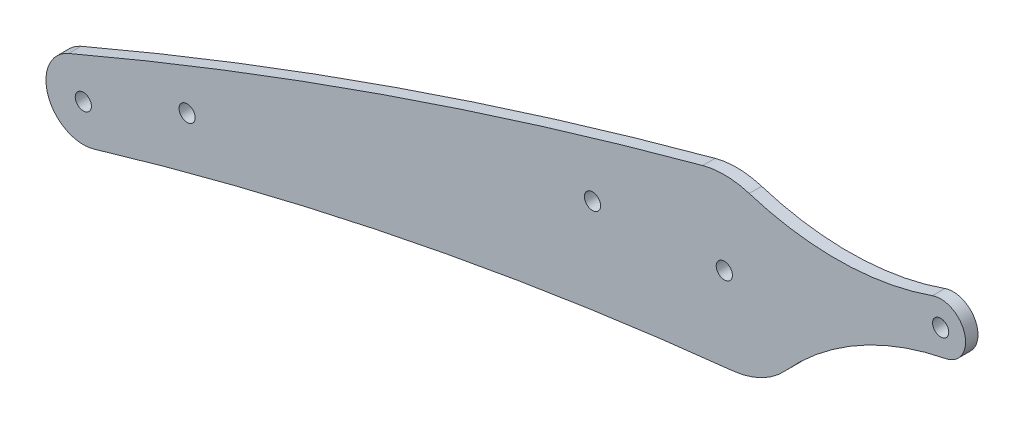
SolidWorks part; units mm, degrees
ref_plane "Front Plane" through (0, 0, 0) normal (0, 0, 1) x (1, 0, 0)
ref_plane "Top Plane" through (0, 0, 0) normal (0, 1, 0) x (1, 0, 0)
ref_plane "Right Plane" through (0, 0, 0) normal (1, 0, 0) x (0, 0, -1)
sketch "Sketch1" plane through (0, 0, 0) normal (0, 0, 1) x (1, 0, 0)
  line L0 (-188.4725, 162.9795) -> (18.0408, 219.089) construction
  line L1 (-188.4725, 162.9795) -> (18.0408, 219.089) construction
  point P0 (-34.07, 204.9305)
sketch "Sketch2" plane through (0, 0, 0) normal (0, 0, 1) x (1, 0, 0)
  circle A0 centre (-188.4725, 162.9795) radius 9 construction
  circle A1 centre (-34.07, 204.9305) radius 20 construction
  circle A2 centre (-34.07, 204.9305) radius 10 construction
  circle A3 centre (18.0408, 219.089) radius 6 construction
  arc A4 (-39.2809, 224.2398) -> (-192.0126, 171.254) centre (260.3422, -886.0422) ccw
  arc A5 (-185.9055, 154.3533) -> (-31.9872, 185.0393) centre (56.5339, -660.3388) cw
  arc A6 (-28.082, 224.0131) -> (16.0541, 224.7506) centre (-7.1238, 290.8019) ccw
  arc A7 (-19.2487, 191.5019) -> (19.1922, 213.2005) centre (32.6259, 144.5017) cw
  arc A8 (-192.0126, 171.254) -> (-185.9055, 154.3533) centre (-188.4725, 162.9795) ccw
  arc A9 (-39.2809, 224.2398) -> (-28.082, 224.0131) centre (-34.07, 204.9305) cw
  arc A10 (16.0541, 224.7506) -> (19.1922, 213.2005) centre (18.0408, 219.089) cw
  arc A11 (-19.2487, 191.5019) -> (-31.9872, 185.0393) centre (-34.07, 204.9305) cw
  arc A12 (-188.4725, 162.9795) -> (18.0408, 219.089) centre (120.0088, -564.3027) cw construction
  point P27 (-163.4725, 173.0835)
  point P28 (-65.82, 203.5304)
  dimension "D1" = 18
  dimension "D2" = 12
  dimension "D3" = 40
  dimension "D4" = 20
  dimension "D5" = 1150
  dimension "D6" = 850
  dimension "D7" = 70
  dimension "D8" = 70
  dimension "D9" = 790
  dimension "D10" = 25
  dimension "D11" = 31.75
extrude "Boss-Extrude1" add sketch "Sketch2" against normal blind 3
hole_wizard "M3.5 Clearance Hole1" positions "Sketch4" profile "Sketch3" hole size "M3.5" standard "ISO"
sketch "Sketch4" plane through (0, 0, 0) normal (0, 0, 1) x (1, 0, 0)
  point P0 (-188.4725, 162.9795)
  point P3 (-163.4725, 173.0835)
  point P6 (-65.82, 203.5304)
  point P9 (-34.07, 204.9305)
  point P12 (18.0408, 219.089)
sketch "Sketch3" plane through (-188.4725, 162.9795, 0) normal (1, 0, 0) x (0, -1, 0)
  line L0 (0, 0) -> (0, 11.1717)
  line L1 (0, 11.1717) -> (1.95, 10)
  line L2 (1.95, 10) -> (1.95, 0)
  line L5 (1.95, 0) -> (0, 0)
  line L10 (0, 11.1717) -> (-1.95, 10) construction
  line L11 (0, -6.35) -> (0, 107.95) construction
  dimension "Hole Dia." = 3.9
  dimension "Hole Depth" = 10
  dimension "Drill Angle" = 118
